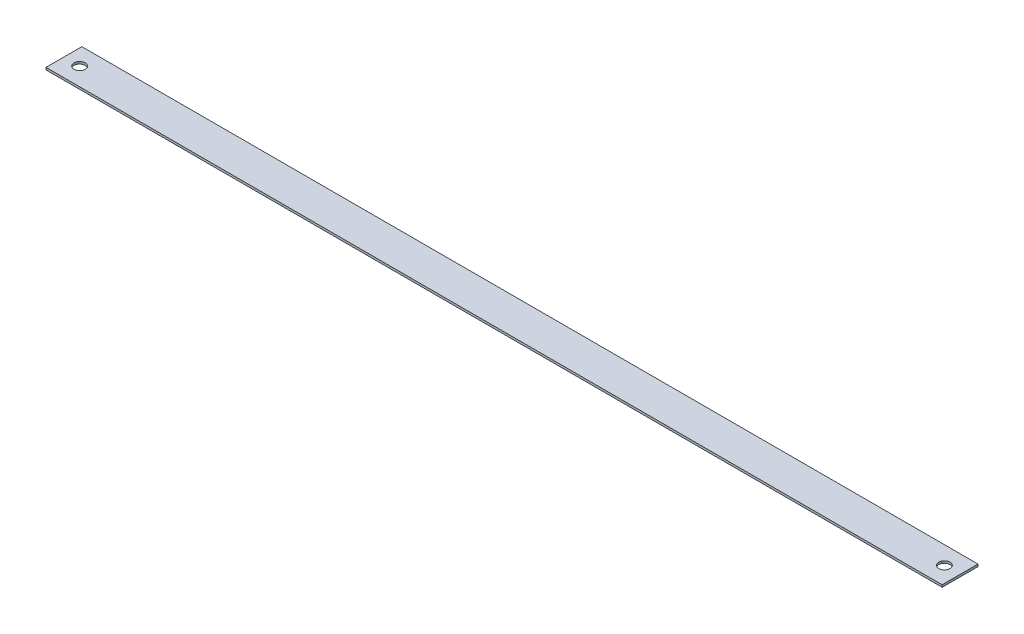
SolidWorks part; units mm, degrees
material "1060 Сплав"
ref_plane "Front" through (0, 0, 0) normal (0, 0, 1) x (1, 0, 0)
ref_plane "Top" through (0, 0, 0) normal (0, 1, 0) x (1, 0, 0)
ref_plane "Right" through (0, 0, 0) normal (1, 0, 0) x (0, 0, -1)
sketch "Эскиз1" plane through (0, 0, 0) normal (0, 1, 0) x (1, 0, 0)
  line L1 (0, 0) -> (-400, 0)
  line L2 (0, 0) -> (0, 16)
  line L3 (0, 16) -> (-400, 16)
  line L4 (-400, 0) -> (-400, 16)
  circle A0 centre (-393, 8) radius 2.5
  circle A1 centre (-7, 8) radius 2.5
  dimension "D3" = 5
  dimension "D4" = 7
  dimension "D5" = 8
  dimension "D1" = 16
  dimension "D2" = 400
  dimension "D6" = 2
extrude "Бобышка-Вытянуть1" add sketch "Эскиз1" along normal blind 1
